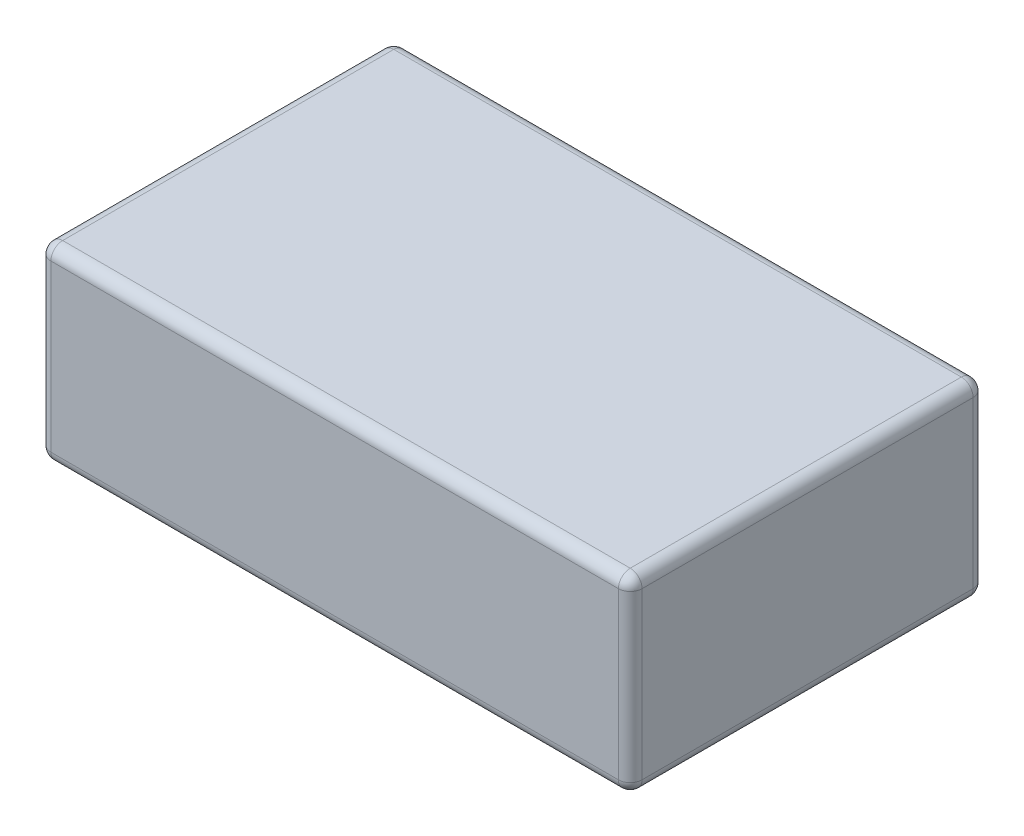
SolidWorks part; units mm, degrees
ref_plane "Front Plane" through (0, 0, 0) normal (0, 0, 1) x (1, 0, 0)
ref_plane "Top Plane" through (0, 0, 0) normal (0, 1, 0) x (1, 0, 0)
ref_plane "Right Plane" through (0, 0, 0) normal (1, 0, 0) x (0, 0, -1)
sketch "Sketch1" plane through (0, 0, 0) normal (1, 0, 0) x (0, 0, -1)
  line L1 (-15, 8) -> (15, 8)
  line L2 (-15, 8) -> (-15, -8)
  line L3 (-15, -8) -> (15, -8)
  line L4 (15, 8) -> (15, -8)
  line L5 (-15, 8) -> (15, -8) construction
  line L6 (-15, -8) -> (15, 8) construction
  point P0 (0, 0)
  dimension "D1" = 30
  dimension "D2" = 16
extrude "Boss-Extrude1" add sketch "Sketch1" against normal blind 50
fillet "Fillet1" radius 1 4 edges at (-25, -8, -15) (-25, -8, 15) (-25, 8, -15) (-25, 8, 15)
fillet "Fillet2" radius 1 16 edges at (-50, 7.7071, -14.7071) (-50, 0, -15) (-50, -7.7071, -14.7071) (-50, -8, 0) (-50, -7.7071, 14.7071) (-50, 0, 15) (-50, 7.7071, 14.7071) (0, 7.7071, -14.7071) (0, 0, -15) (0, -7.7071, -14.7071) (0, -8, 0) (0, -7.7071, 14.7071) (0, 0, 15) (0, 7.7071, 14.7071) (-50, 8, 0) (0, 8, 0)
